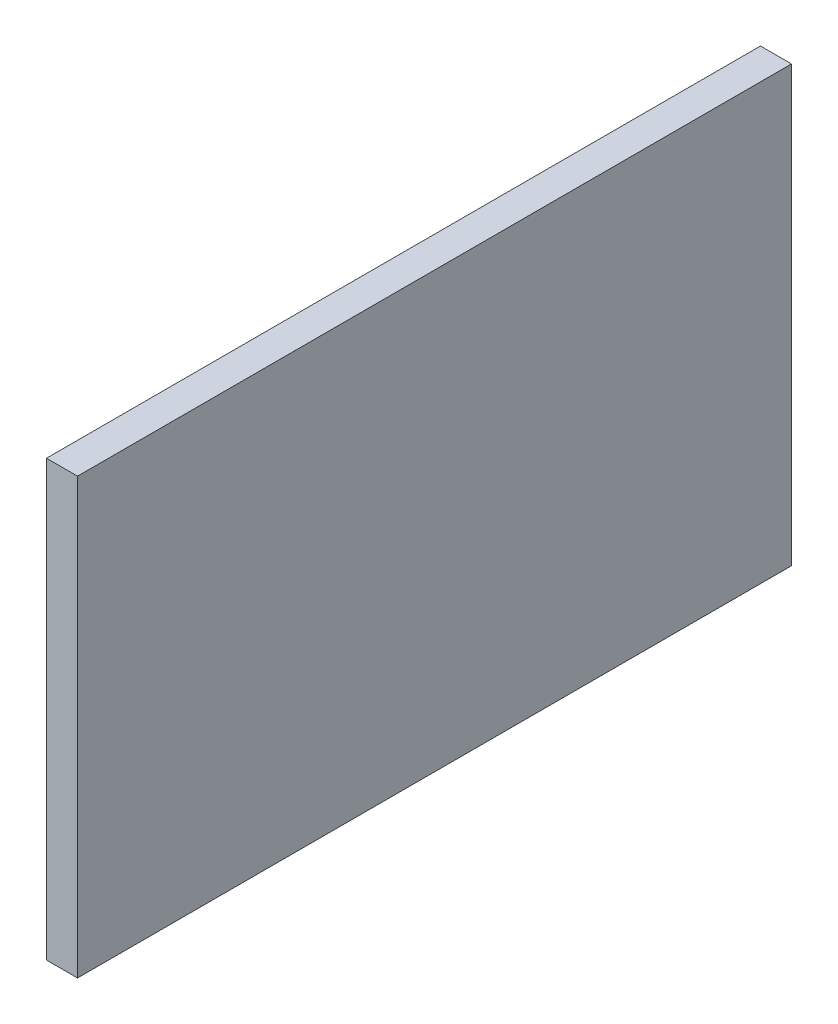
SolidWorks part; units mm, degrees
ref_plane "Front Plane" through (0, 0, 0) normal (0, 0, 1) x (1, 0, 0)
ref_plane "Top Plane" through (0, 0, 0) normal (0, 1, 0) x (1, 0, 0)
ref_plane "Right Plane" through (0, 0, 0) normal (1, 0, 0) x (0, 0, -1)
sketch "Sketch1" plane through (0, 0, 0) normal (1, 0, 0) x (0, 0, -1)
  line L1 (34.5, -21) -> (-34.5, -21)
  line L2 (34.5, -21) -> (34.5, 21)
  line L3 (34.5, 21) -> (-34.5, 21)
  line L4 (-34.5, -21) -> (-34.5, 21)
  line L5 (34.5, -21) -> (-34.5, 21) construction
  line L6 (34.5, 21) -> (-34.5, -21) construction
  point P0 (0, 0)
  dimension "D1" = 69
  dimension "D2" = 42
extrude "Boss-Extrude1" add sketch "Sketch1" along normal blind 3
